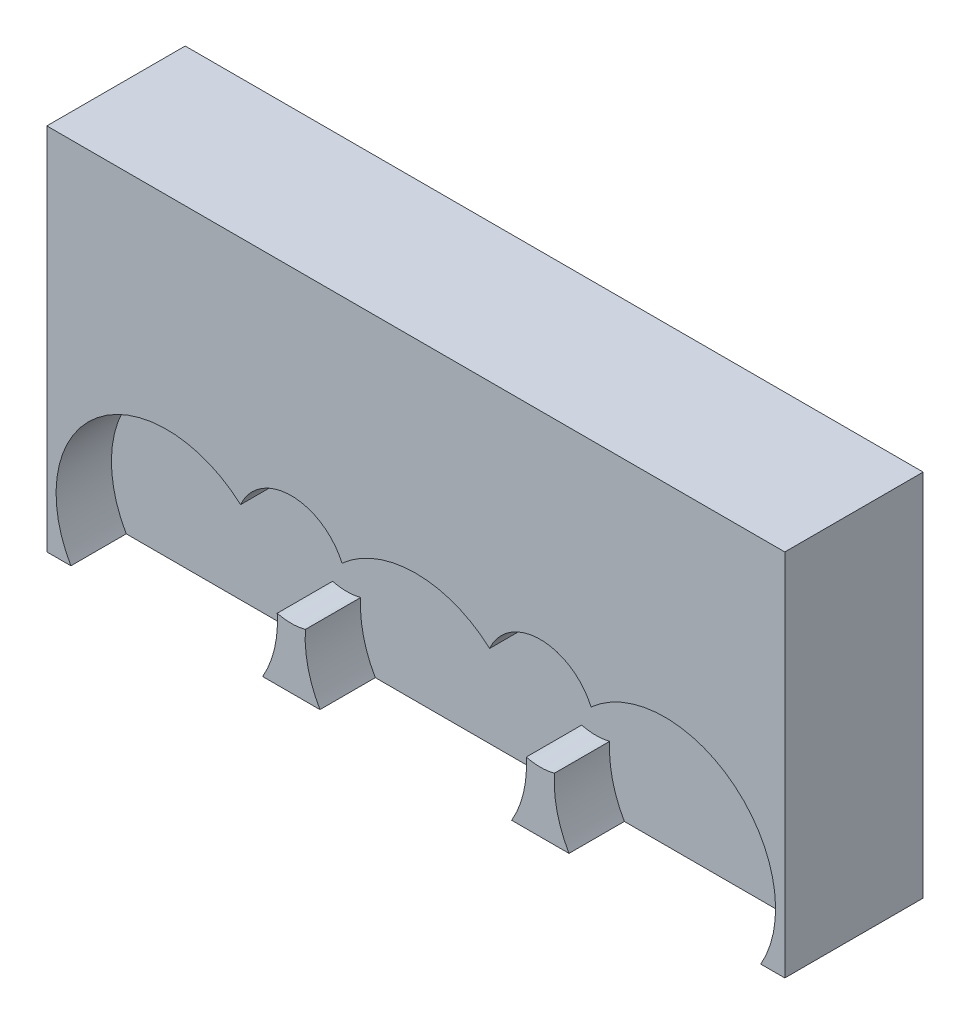
SolidWorks part; units mm, degrees
ref_plane "Front Plane" through (0, 0, 0) normal (0, 0, 1) x (1, 0, 0)
ref_plane "Top Plane" through (0, 0, 0) normal (0, 1, 0) x (1, 0, 0)
ref_plane "Right Plane" through (0, 0, 0) normal (1, 0, 0) x (0, 0, -1)
sketch "Sketch1" plane through (0, 0, 0) normal (0, 0, 1) x (1, 0, 0)
  line L1 (-40, -20) -> (40, -20)
  line L2 (-40, -20) -> (-40, 20)
  line L3 (-40, 20) -> (40, 20)
  line L4 (40, -20) -> (40, 20)
  line L5 (-40, -20) -> (40, 20) construction
  line L6 (-40, 20) -> (40, -20) construction
  point P0 (0, 0)
  dimension "D1" = 40
  dimension "D2" = 80
extrude "Boss-Extrude1" add sketch "Sketch1" along normal blind 15
sketch "Sketch2" plane through (0, 0, 15) normal (0, 0, 1) x (1, 0, 0)
  line L1 (-40, -20) -> (40, -20) construction
  line L2 (0, 0) -> (0, -50000) construction
  circle A0 centre (0, -14) radius 12
  circle A1 centre (27, -14) radius 12
  circle A2 centre (0, -14) radius 11 construction
  circle A3 centre (27, -14) radius 11 construction
  circle A4 centre (-27, -14) radius 12
  circle A5 centre (-27, -14) radius 11 construction
  circle A6 centre (-13.5, -7.4617) radius 5 construction
  circle A7 centre (-13.5, -7.4617) radius 6
  circle A8 centre (13.5, -7.4617) radius 6
  circle A9 centre (13.5, -7.4617) radius 5 construction
  point P7 (0, -26)
  line M7 (-40, -20) -> (40, -20)
  dimension "D1" = 24
  dimension "D2" = 6
  dimension "D3" = 27
  dimension "D4" = 1
  dimension "D5" = 27
  dimension "D6" = 10
  dimension "D7" = 15
  dimension "D8" = 15
  dimension "D9" = 1
extrude "Cut-Extrude1" cut sketch "Sketch2" against normal blind 6 contours A0 A7 A4 | A7 A4 M7 | A0 A8 A7 M7 | A1 A8 M7 | A8 A1 A0 | A8 A1 | A0 A7 | A4 A7 | A8 A0
